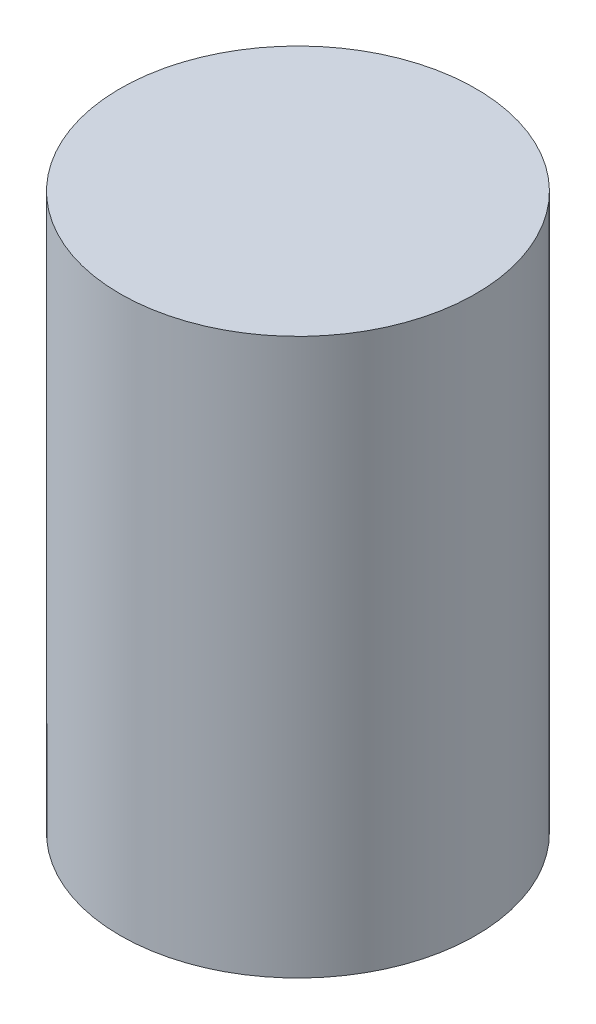
SolidWorks part; units mm, degrees
material "Nylon 6/10"
ref_plane "Front Plane" through (0, 0, 0) normal (0, 0, 1) x (1, 0, 0)
ref_plane "Top Plane" through (0, 0, 0) normal (0, 1, 0) x (1, 0, 0)
ref_plane "Right Plane" through (0, 0, 0) normal (1, 0, 0) x (0, 0, -1)
sketch "Sketch1" plane through (0, 0, 0) normal (0, 1, 0) x (1, 0, 0)
  circle A0 centre (0, 0) radius 80
  dimension "D1" = 160
extrude "Boss-Extrude1" add sketch "Sketch1" along normal blind 250
